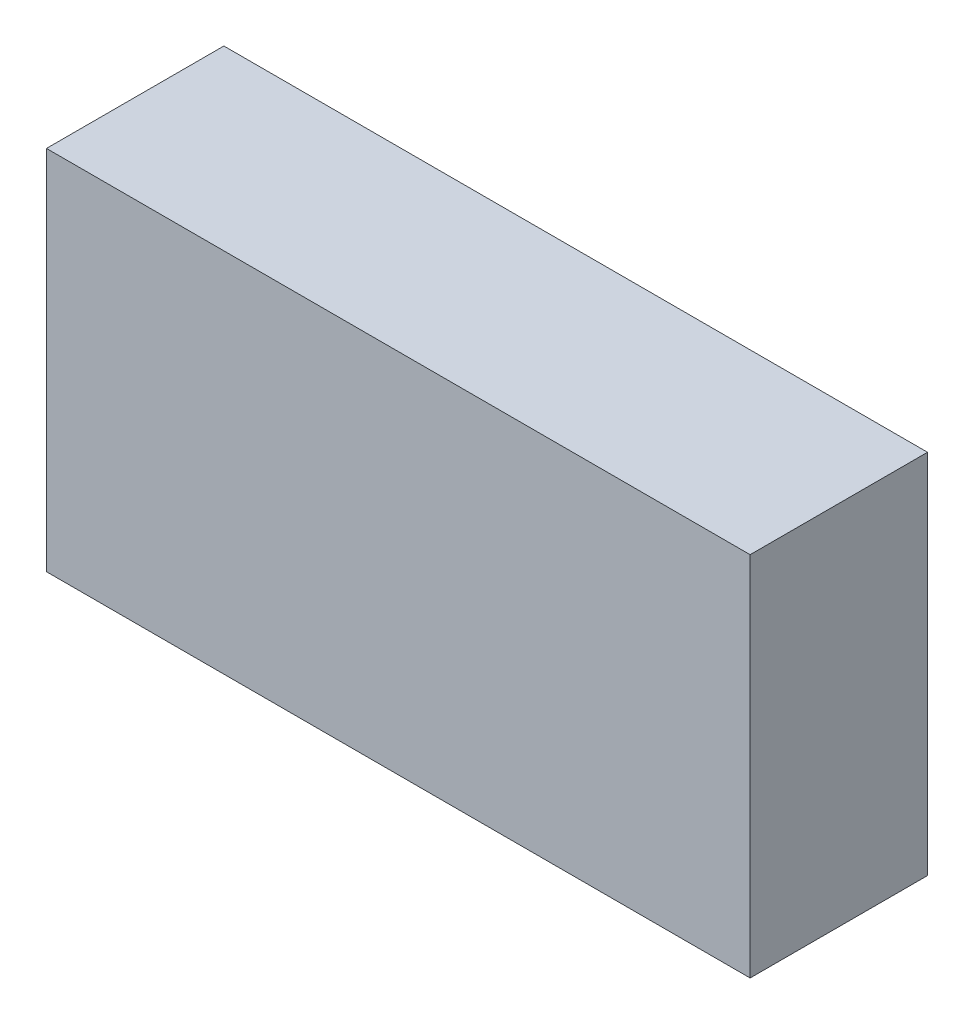
SolidWorks part; units mm, degrees
ref_plane "前视基准面" through (0, 0, 0) normal (0, 0, 1) x (1, 0, 0)
ref_plane "上视基准面" through (0, 0, 0) normal (0, 1, 0) x (1, 0, 0)
ref_plane "右视基准面" through (0, 0, 0) normal (1, 0, 0) x (0, 0, -1)
sketch "草图1" plane through (0, 0, 0) normal (0, 0, 1) x (1, 0, 0)
  line L1 (-55.1795, 75.5128) -> (182.8205, 75.5128)
  line L2 (-55.1795, 75.5128) -> (-55.1795, -48.4872)
  line L3 (-55.1795, -48.4872) -> (182.8205, -48.4872)
  line L4 (182.8205, 75.5128) -> (182.8205, -48.4872)
  dimension "D1" = 124
  dimension "D2" = 238
extrude "凸台-拉伸1" add sketch "草图1" along normal blind 60
